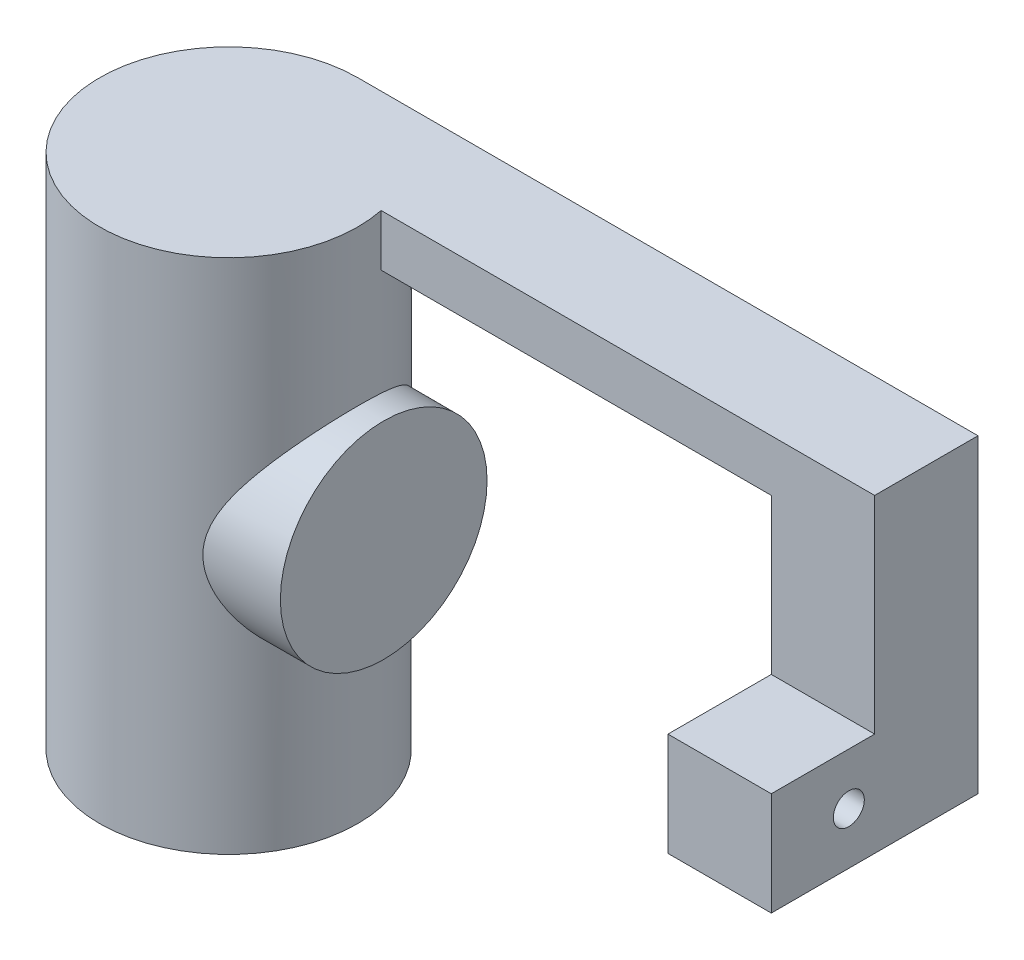
SolidWorks part; units mm, degrees
ref_plane "Front Plane" through (0, 0, 0) normal (0, 0, 1) x (1, 0, 0)
ref_plane "Top Plane" through (0, 0, 0) normal (0, 1, 0) x (1, 0, 0)
ref_plane "Right Plane" through (0, 0, 0) normal (1, 0, 0) x (0, 0, -1)
sketch "Sketch1" plane through (0, 0, 0) normal (0, 1, 0) x (1, 0, 0)
  circle A0 centre (0, 0) radius 25
  dimension "D1" = 50
extrude "Boss-Extrude1" add sketch "Sketch1" along normal mid plane 100
sketch "Sketch2" plane through (0, 0, 0) normal (1, 0, 0) x (0, 0, -1)
  circle A0 centre (0, 0) radius 20
  dimension "D1" = 40
extrude "Boss-Extrude2" add sketch "Sketch2" along normal blind 30
sketch "Sketch3" plane through (0, 0, 0) normal (1, 0, 0) x (0, 0, -1)
  line L0 (25, -50) -> (25, 50) construction
  line L1 (5, 50) -> (25, 50)
  line L2 (5, 50) -> (5, 40)
  line L3 (5, 40) -> (25, 40)
  line L4 (25, 50) -> (25, 40)
  line L5 (25, 50) -> (-25, 50) construction
  dimension "D1" = 10
  dimension "D2" = 20
extrude "Boss-Extrude3" add sketch "Sketch3" along normal offset from surface (120 mm away) 90 up to face at (30, 0, -20) offset beyond the face yes
sketch "Sketch4" plane through (0, 40, 0) normal (0, -1, 0) x (1, 0, 0)
  line L0 (120, -25) -> (0, -25) construction
  line L1 (120, -5) -> (100, -5)
  line L2 (120, -5) -> (120, -25)
  line L3 (120, -25) -> (100, -25)
  line L4 (100, -5) -> (100, -25)
  dimension "D1" = 20
extrude "Boss-Extrude4" add sketch "Sketch4" along normal blind 50
sketch "Sketch5" plane through (0, 0, -25) normal (0, 0, -1) x (-1, 0, 0)
  line L0 (-120, -10) -> (-120, 50) construction
  line L1 (-100, -10) -> (-120, -10)
  line L2 (-100, -10) -> (-100, 10)
  line L3 (-100, 10) -> (-120, 10)
  line L4 (-120, -10) -> (-120, 10)
  dimension "D1" = 20
extrude "Boss-Extrude5" add sketch "Sketch5" against normal offset from surface (40 mm away) 20 up to face at (81.4983, 26.6667, -5) offset beyond the face yes
sketch "Sketch6" plane through (120, 0, 0) normal (1, 0, 0) x (0, 0, -1)
  circle A0 centre (0, 0) radius 3
  dimension "D1" = 6
extrude "Cut-Extrude1" cut sketch "Sketch6" against normal up to surface (20 mm away) up to face at (100, 13.3333, -5)
